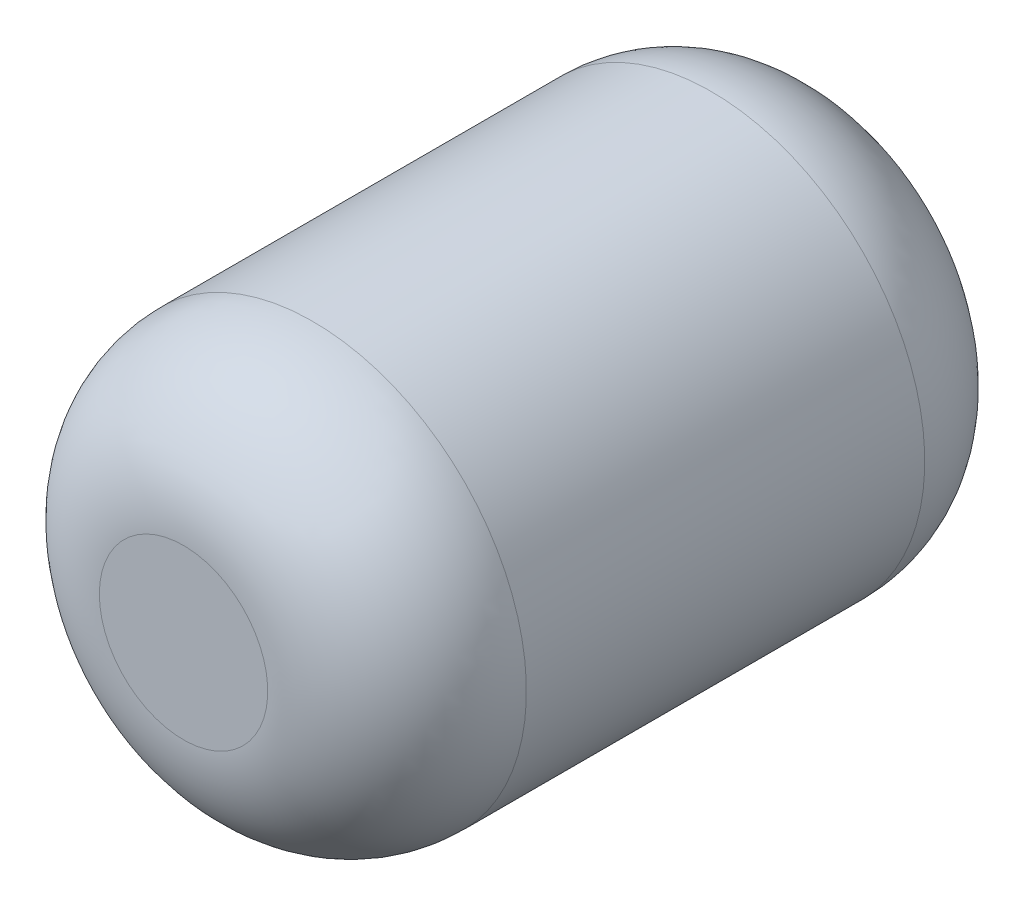
SolidWorks part; units mm, degrees
ref_plane "Front Plane" through (0, 0, 0) normal (0, 0, 1) x (1, 0, 0)
ref_plane "Top Plane" through (0, 0, 0) normal (0, 1, 0) x (1, 0, 0)
ref_plane "Right Plane" through (0, 0, 0) normal (1, 0, 0) x (0, 0, -1)
ref_axis "Axis1" through (0, 0, -193.4257) along (0, 0, 1)
sketch "Sketch1" plane through (0, 0, 0) normal (1, 0, 0) x (0, 0, -1)
  line L1 (127, 82.55) -> (-127, 82.55) construction
  line L2 (127, 82.55) -> (127, -82.55) construction
  line L3 (127, -82.55) -> (-127, -82.55) construction
  line L4 (-127, 82.55) -> (-127, -82.55) construction
  line L5 (127, 82.55) -> (-127, -82.55) construction
  line L6 (127, -82.55) -> (-127, 82.55) construction
  line L7 (-77, 82.55) -> (77, 82.55)
  line L10 (-127, 0) -> (-127, 32.55)
  line L13 (127, 0) -> (127, 32.55)
  line L14 (-122, 0) -> (-122, 32.55)
  line L15 (-77, 77.55) -> (77, 77.55)
  line L16 (122, 0) -> (122, 32.55)
  line L17 (-127, 0) -> (-122, 0)
  line L18 (122, 0) -> (127, 0)
  line L19 (-122, 0) -> (122, 0) construction
  arc A0 (-127, 32.55) -> (-77, 82.55) centre (-77, 32.55) cw
  arc A1 (127, 32.55) -> (77, 82.55) centre (77, 32.55) ccw
  arc A2 (-122, 32.55) -> (-77, 77.55) centre (-77, 32.55) cw
  arc A3 (122, 32.55) -> (77, 77.55) centre (77, 32.55) ccw
  point P0 (0, 0)
  point P14 (0, 82.55)
  dimension "D3" = 50
  dimension "D1" = 254
  dimension "D2" = 165.1
  dimension "D4" = 5
revolve "Revolve1" add sketch "Sketch1" angle 360 about axis through (0, 0, -193.4257) along (0, 0, 1)
equation "\"D1@Sketch1\"=10*25.4"
equation "\"D2@Sketch1\"=6.5*25.4"
